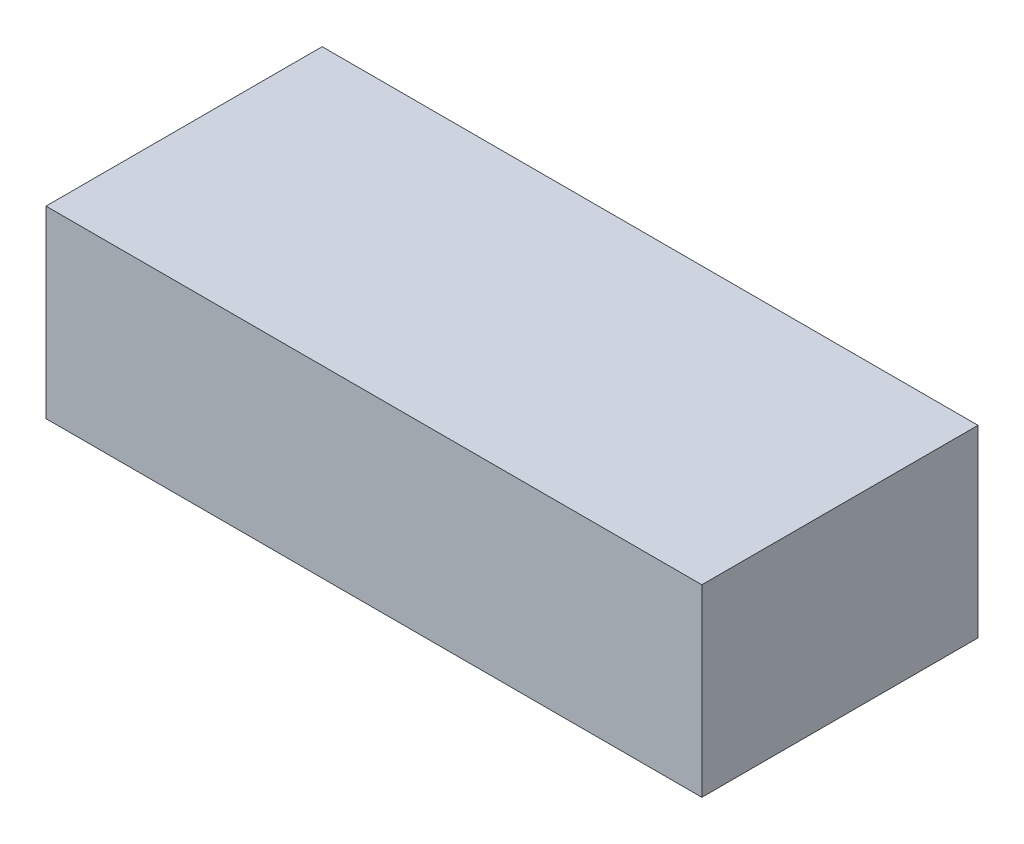
SolidWorks part; units mm, degrees
material "Custom Plastic"
ref_plane "Front Plane" through (0, 0, 0) normal (0, 0, 1) x (1, 0, 0)
ref_plane "Top Plane" through (0, 0, 0) normal (0, 1, 0) x (1, 0, 0)
ref_plane "Right Plane" through (0, 0, 0) normal (1, 0, 0) x (0, 0, -1)
sketch "Sketch1" plane through (0, 0, 0) normal (0, 1, 0) x (1, 0, 0)
  line L1 (0, 0) -> (361.95, 0)
  line L2 (0, 0) -> (0, 152.4)
  line L3 (0, 152.4) -> (361.95, 152.4)
  line L4 (361.95, 0) -> (361.95, 152.4)
  dimension "D1" = 361.95
  dimension "D2" = 152.4
extrude "Boss-Extrude1" add sketch "Sketch1" along normal blind 101.6
